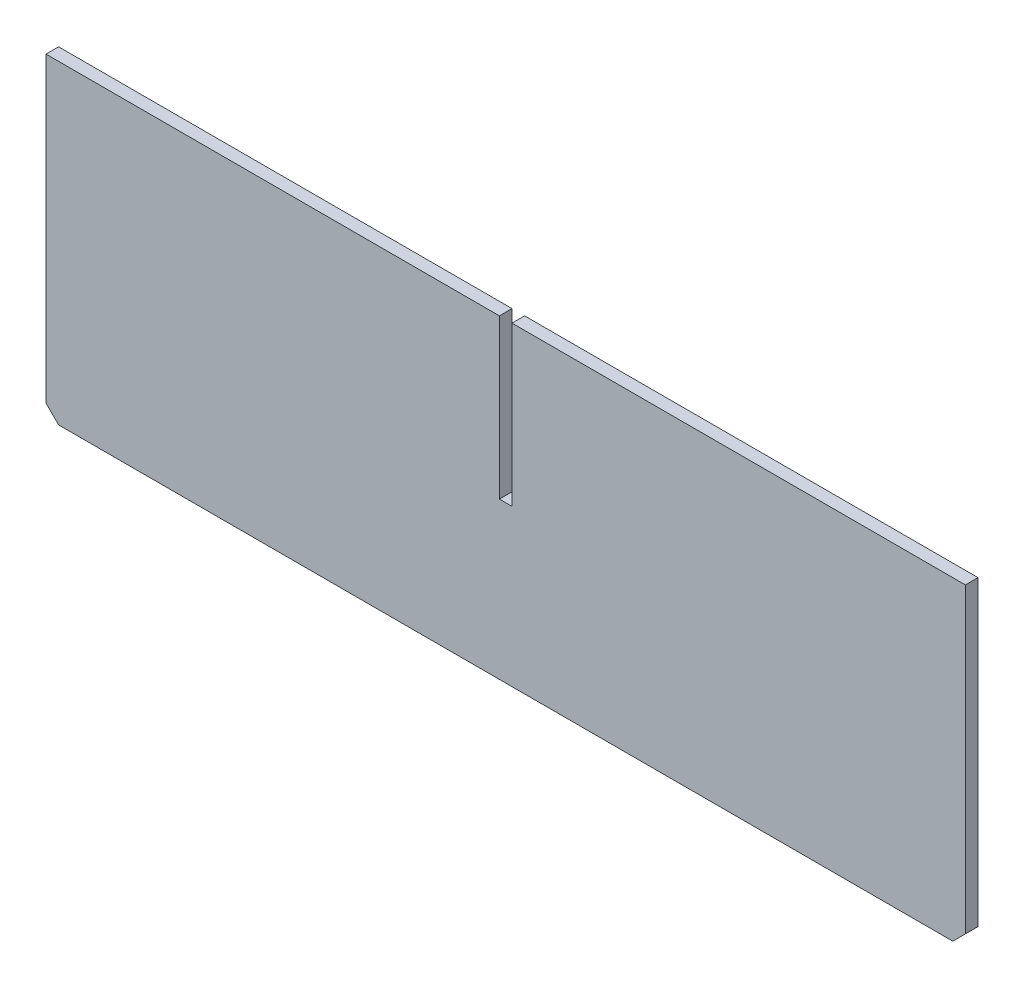
SolidWorks part; units mm, degrees
ref_plane "前视基准面" through (0, 0, 0) normal (0, 0, 1) x (1, 0, 0)
ref_plane "上视基准面" through (0, 0, 0) normal (0, 1, 0) x (1, 0, 0)
ref_plane "右视基准面" through (0, 0, 0) normal (1, 0, 0) x (0, 0, -1)
other "Configuration Table"
sketch "草图1" plane through (0, 0, 0) normal (0, 0, 1) x (1, 0, 0)
  line L1 (0, 0) -> (146, 0)
  line L2 (0, 0) -> (0, -50)
  line L3 (0, -50) -> (146, -50)
  line L4 (146, 0) -> (146, -50)
  dimension "D1" = 146
  dimension "D2" = 50
extrude "凸台-拉伸1" add sketch "草图1" along normal blind 2
chamfer "倒角1" distance 2 angle 45 2 edges at (146, -50, 1) (0, -50, 1)
sketch "草图2" plane through (0, 0, 2) normal (0, 0, 1) x (1, 0, 0)
  line L0 (146, 0) -> (0, 0) construction
  line L1 (72, 0) -> (74, 0)
  line L2 (72, 0) -> (72, -25.2)
  line L3 (72, -25.2) -> (74, -25.2)
  line L4 (74, 0) -> (74, -25.2)
  point P6 (73, 0)
  point P7 (73, 0)
  dimension "D1" = 0
  dimension "D2" = 2
  dimension "D3" = 25.2
extrude "切除-拉伸1" cut sketch "草图2" against normal through all
